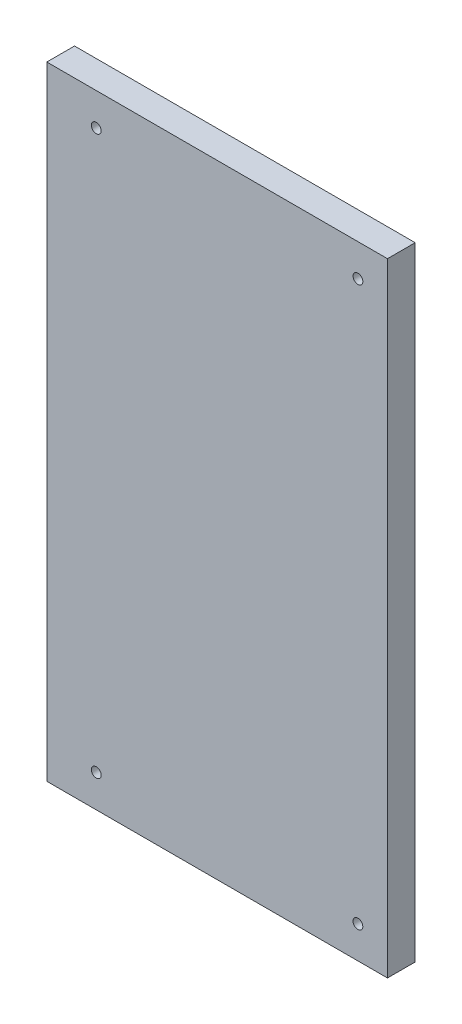
SolidWorks part; units mm, degrees
ref_plane "Front Plane" through (0, 0, 0) normal (0, 0, 1) x (1, 0, 0)
ref_plane "Top Plane" through (0, 0, 0) normal (0, 1, 0) x (1, 0, 0)
ref_plane "Right Plane" through (0, 0, 0) normal (1, 0, 0) x (0, 0, -1)
sketch "Sketch1" plane through (0, 0, 0) normal (0, 0, 1) x (1, 0, 0)
  line L1 (-386.5647, -11.1125) -> (-152.3882, -11.1125)
  line L3 (-386.5647, 417.1125) -> (-152.3882, 417.1125)
  line L4 (-152.3882, -11.1125) -> (-152.3882, 417.1125)
  line L5 (-385.6004, 203) -> (-152.3882, 203) construction
  line L6 (-152.3882, 417.1125) -> (-152.3882, -11.1125) construction
  line L8 (-386.5647, 417.1125) -> (-386.5647, -11.1125)
  line L9 (-386.5647, 0) -> (-386.5647, 58.22) construction
  point P12 (-385.6004, 203)
extrude "Boss-Extrude1" add sketch "Sketch1" along normal blind 19.05
extrude "Cut-Extrude2" cut sketch "Sketch4" against normal through all
sketch "Sketch4" plane through (-216.2065, 203, -1.905) normal (0, 0, -1) x (0, -1, 0)
  line L0 (197.92, -43.4982) -> (186.109, -43.4982) construction
  circle A0 centre (192.0145, -43.4982) radius 3.3655
extrude "Cut-Extrude3" cut sketch "Sketch5" against normal through all
sketch "Sketch5" plane through (-216.2065, 203, -5.207) normal (0, 0, -1) x (0, -1, 0)
  line L8 (194.9609, 131.3631) -> (188.6537, 141.3891) construction
  circle A0 centre (191.8073, 136.3761) radius 3.3782
ref_plane "Plane1" through (0, 203, 0) normal (0, 1, 0) x (1, 0, 0)
mirror "Mirror1" about plane through (0, 203, 0) normal (0, 1, 0) of "Cut-Extrude3", "Cut-Extrude2"
sketch "Sketch6" plane through (0, 0, 19.05) normal (0, 0, 1) x (1, 0, 0)
  circle A1 centre (-172.7082, 10.9855) radius 3.3655
  circle A2 centre (-172.7082, 10.9855) radius 3.3655
  circle A3 centre (-352.5826, 11.1927) radius 3.3782
  circle A4 centre (-352.5826, 11.1927) radius 3.3782
  circle A5 centre (-172.7082, 395.0145) radius 3.3655
  circle A6 centre (-172.7082, 395.0145) radius 3.3655
  circle A7 centre (-352.5826, 394.8073) radius 3.3782
  circle A8 centre (-352.5826, 394.8073) radius 3.3782
  dimension "D1" = 0
  dimension "D2" = 0
  dimension "D3" = 0
  dimension "D4" = 0
